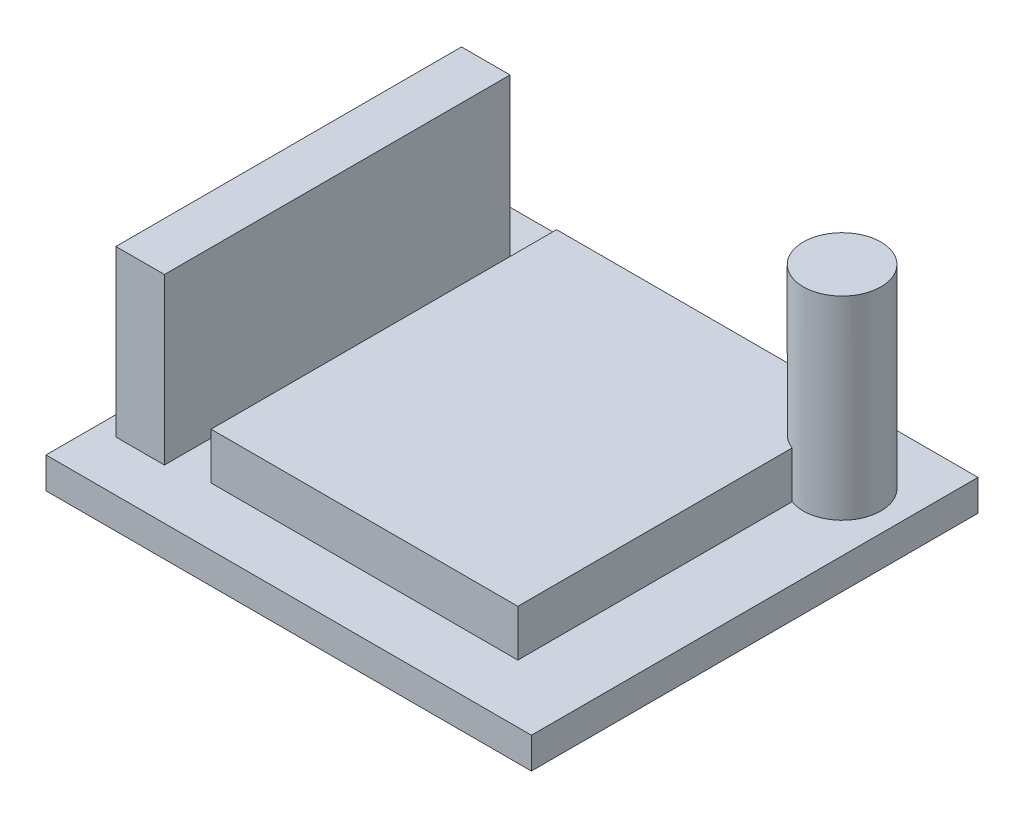
SolidWorks part; units mm, degrees
ref_plane "Front Plane" through (0, 0, 0) normal (0, 0, 1) x (1, 0, 0)
ref_plane "Top Plane" through (0, 0, 0) normal (0, 1, 0) x (1, 0, 0)
ref_plane "Right Plane" through (0, 0, 0) normal (1, 0, 0) x (0, 0, -1)
other "Configuration Table"
sketch "Sketch1" plane through (0, 0, 0) normal (0, 1, 0) x (1, 0, 0)
  line L1 (0, 0) -> (25, 0)
  line L2 (0, 0) -> (0, 23)
  line L3 (0, 23) -> (25, 23)
  line L4 (25, 0) -> (25, 23)
extrude "PCB" add sketch "Sketch1" along normal blind 1.6
sketch "Sketch2" plane through (0, 0, 0) normal (0, 1, 0) x (1, 0, 0)
  line L1 (5.5, 3) -> (21.3, 3)
  line L2 (5.5, 3) -> (5.5, 20.8)
  line L3 (5.5, 20.8) -> (21.3, 20.8)
  line L4 (21.3, 3) -> (21.3, 20.8)
extrude "SIM800L_module" add sketch "Sketch2" along normal blind 2.4 from offset 1.6
sketch "Sketch3" plane through (0, 0, 0) normal (0, 1, 0) x (1, 0, 0)
  line L1 (1, 2.6) -> (3.5, 2.6)
  line L2 (1, 2.6) -> (1, 20.4)
  line L3 (1, 20.4) -> (3.5, 20.4)
  line L4 (3.5, 2.6) -> (3.5, 20.4)
extrude "Header_7pin" add sketch "Sketch3" along normal blind 8.5 from offset 1.6
sketch "Sketch4" plane through (0, 0, 0) normal (0, 1, 0) x (1, 0, 0)
  circle A0 centre (22, 19) radius 2
extrude "Antenna_spring" add sketch "Sketch4" along normal blind 10 from offset 1.6
sketch "Sketch5" plane through (0, 0, 0) normal (0, 1, 0) x (1, 0, 0)
  line L1 (3, 2) -> (22, 2)
  line L2 (3, 2) -> (3, 19)
  line L3 (3, 19) -> (22, 19)
  line L4 (22, 2) -> (22, 19)
extrude "SIM_holder" add sketch "Sketch5" against normal blind 2
